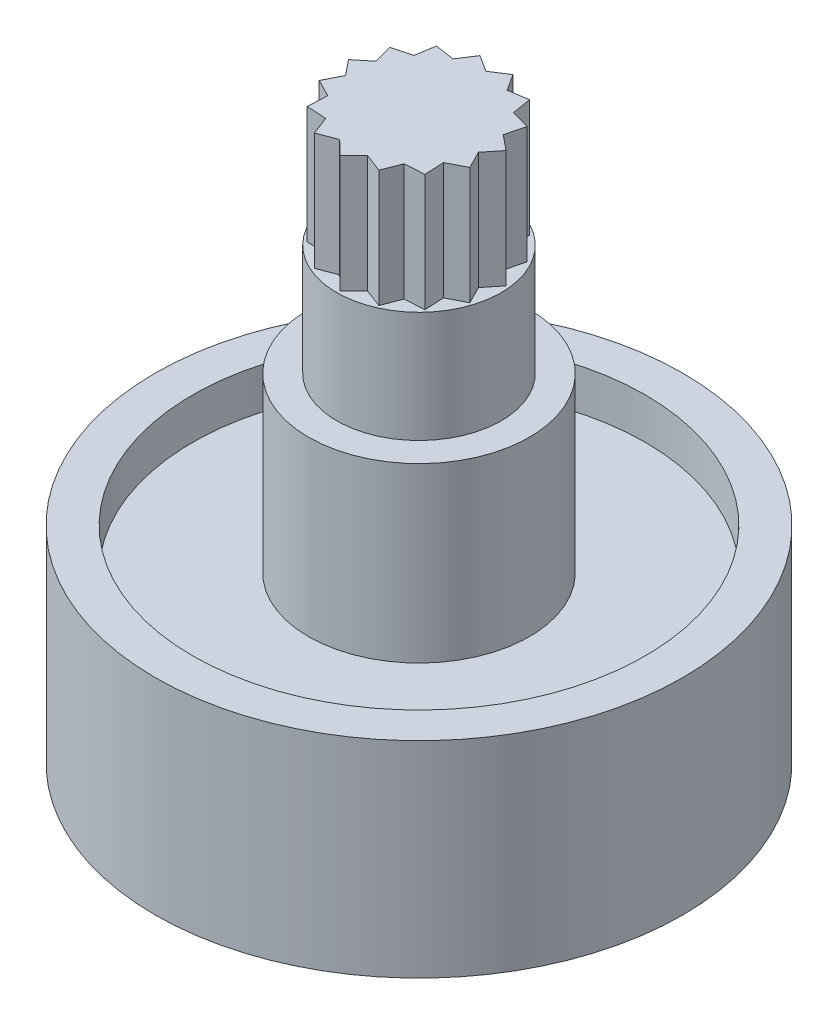
SolidWorks part; units mm, degrees
material "Nylon 101"
ref_plane "Front Plane" through (0, 0, 0) normal (0, 0, 1) x (1, 0, 0)
ref_plane "Top Plane" through (0, 0, 0) normal (0, 1, 0) x (1, 0, 0)
ref_plane "Right Plane" through (0, 0, 0) normal (1, 0, 0) x (0, 0, -1)
sketch "Sketch1" plane through (0, 0, 0) normal (0, 0, 1) x (1, 0, 0)
  line L0 (0, 0) -> (0, 27.5) construction
  line L1 (12.827, 0) -> (12.827, 10)
  line L2 (12.827, 10) -> (11, 10)
  line L3 (11, 10) -> (11, 8)
  line L4 (11, 8) -> (5.375, 8)
  line L5 (5.375, 8) -> (5.375, 16.4)
  line L6 (5.375, 16.4) -> (4, 16.4)
  line L7 (4, 16.4) -> (4, 21.8)
  line L8 (4, 21.8) -> (3.85, 21.8)
  line L9 (3.85, 21.8) -> (3.85, 27.5)
  line L10 (3.85, 27.5) -> (0, 27.5)
  line L11 (0, 14.75) -> (0, 27.5)
  line L12 (0, 14.75) -> (3.55, 14.75)
  line L13 (3.55, 14.75) -> (3.55, 3.5)
  line L14 (3.55, 3.5) -> (7, 3.5)
  line L15 (7, 3.5) -> (7, 0)
  line L16 (7, 0) -> (12.827, 0)
  dimension "D1" = 10
  dimension "D2" = 6.4
  dimension "D3" = 2
  dimension "D4" = 5.4
  dimension "D5" = 27.5
  dimension "D6" = 7.7
  dimension "D7" = 8
  dimension "D8" = 7.1
  dimension "D9" = 14.75
  dimension "D10" = 14
  dimension "D11" = 3.5
  dimension "D12" = 10.75
  dimension "D13" = 22
  dimension "D14" = 25.654
revolve "52 Tooth" add sketch "Sketch1" angle 360 about L0
sketch "Sketch2" plane through (0, 27.5, 0) normal (0, 1, 0) x (1, 0, 0)
  line L0 (-0.8005, 3.7659) -> (0, 3.25)
  line L1 (0, 3.25) -> (0.8005, 3.7659)
  line L2 (0, 0) -> (-0.8005, 3.7659) construction
  line L3 (0, 0) -> (0, 3.25) construction
  line L4 (0, 0) -> (0.8005, 3.7659) construction
  circle A0 centre (0, 0) radius 3.85 construction
  circle A1 centre (0, 0) radius 3.85
  circle A2 centre (0, 0) radius 3.25
  circle M1 centre (0, 0) radius 3.85
  dimension "D3" = 6.5
  dimension "D1" = 24
  dimension "D2" = 12
extrude "Cut-Extrude1" cut sketch "Sketch2" against normal up to surface (5.7 mm away) contours L0 L1 M1 up to face at (0, 21.8, -3.85)
pattern_circular "CirPattern1" count 15 over 360 about axis through (0, 0, 0) along (0, 1, 0) of "Cut-Extrude1"
